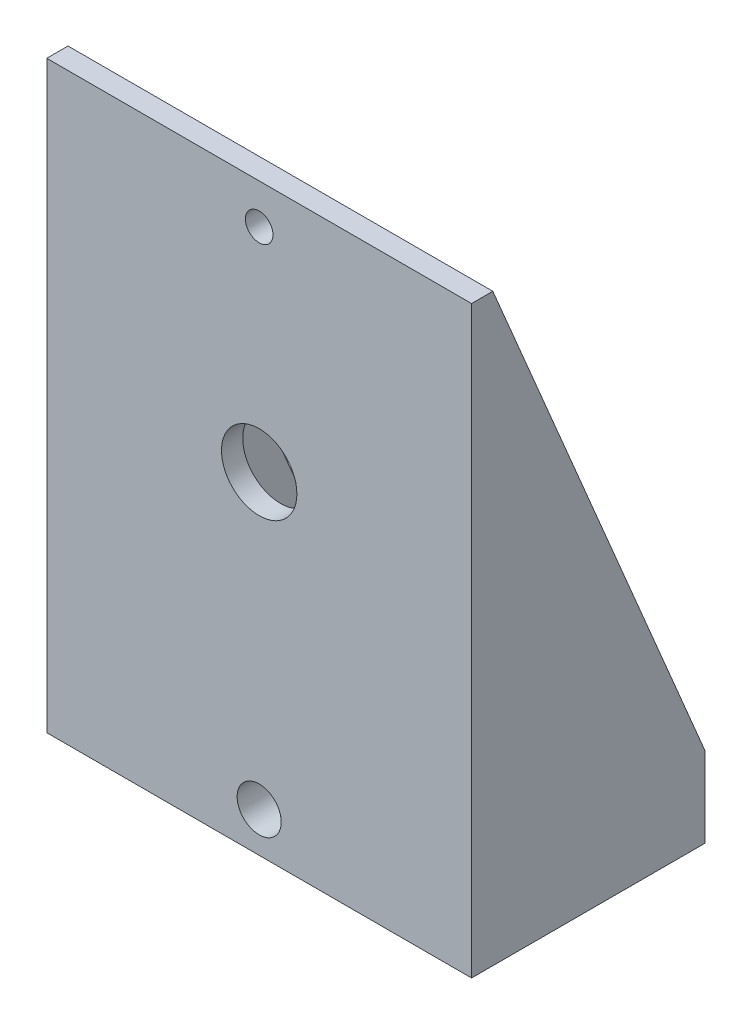
SolidWorks part; units mm, degrees
ref_plane "前视基准面" through (0, 0, 0) normal (0, 0, 1) x (1, 0, 0)
ref_plane "上视基准面" through (0, 0, 0) normal (0, 1, 0) x (1, 0, 0)
ref_plane "右视基准面" through (0, 0, 0) normal (1, 0, 0) x (0, 0, -1)
other "Configuration Table"
sketch "草图1" plane through (0, 0, 0) normal (0, 0, 1) x (1, 0, 0)
  line L1 (0, 0) -> (80, 0)
  line L2 (0, 0) -> (0, -110)
  line L3 (0, -110) -> (80, -110)
  line L4 (80, 0) -> (80, -110)
  dimension "D1" = 80
  dimension "D2" = 110
extrude "凸台-拉伸1" add sketch "草图1" along normal blind 4
sketch "草图2" plane through (0, 0, 4) normal (0, 0, 1) x (1, 0, 0)
  line L0 (40, 0) -> (40, -110) construction
  line L1 (80, 0) -> (0, 0) construction
  line L2 (0, -110) -> (80, -110) construction
  circle A0 centre (40, -47.5) radius 7.1
  circle A1 centre (40, -7.5) radius 2.6
  dimension "D1" = 14.2
  dimension "D2" = 5.2
  dimension "D3" = 7.5
  dimension "D4" = 40
extrude "切除-拉伸1" cut sketch "草图2" against normal through all
sketch "草图3" plane through (0, 0, 0) normal (0, 0, -1) x (-1, 0, 0)
  line L0 (-80, -110) -> (-80, 0) construction
  line L1 (-80, -95) -> (0, -95)
  line L2 (-80, -95) -> (-80, -110)
  line L3 (-80, -110) -> (0, -110)
  line L4 (0, -95) -> (0, -110)
  dimension "D1" = 15
extrude "凸台-拉伸2" add sketch "草图3" along normal blind 40
sketch "草图4" plane through (0, 0, -40) normal (0, 0, -1) x (-1, 0, 0)
  line L0 (-40, -95) -> (-40, -110) construction
  line L1 (0, -95) -> (-80, -95) construction
  line L2 (-80, -110) -> (0, -110) construction
  circle A0 centre (-40, -102.5) radius 4.15
  dimension "D1" = 8.3
extrude "切除-拉伸2" cut sketch "草图4" against normal through all
sketch "草图5" plane through (80, 0, 0) normal (1, 0, 0) x (0, 0, -1)
  line L0 (0, 0) -> (0, -95)
  line L1 (40, -95) -> (0, -95) construction
  line L2 (0, -95) -> (0, 0) construction
  line L3 (0, -95) -> (40, -95)
  line L4 (40, -95) -> (40, -110) construction
  line L5 (40, -95) -> (0, 0)
extrude "凸台-拉伸3" add sketch "草图5" against normal blind 7
sketch "草图6" plane through (0, 0, 0) normal (-1, 0, 0) x (0, 0, 1)
  line L0 (0, 0) -> (0, -95)
  line L1 (0, -95) -> (-40, -95)
  line L2 (-40, -95) -> (0, 0)
extrude "凸台-拉伸4" add sketch "草图6" against normal blind 7
